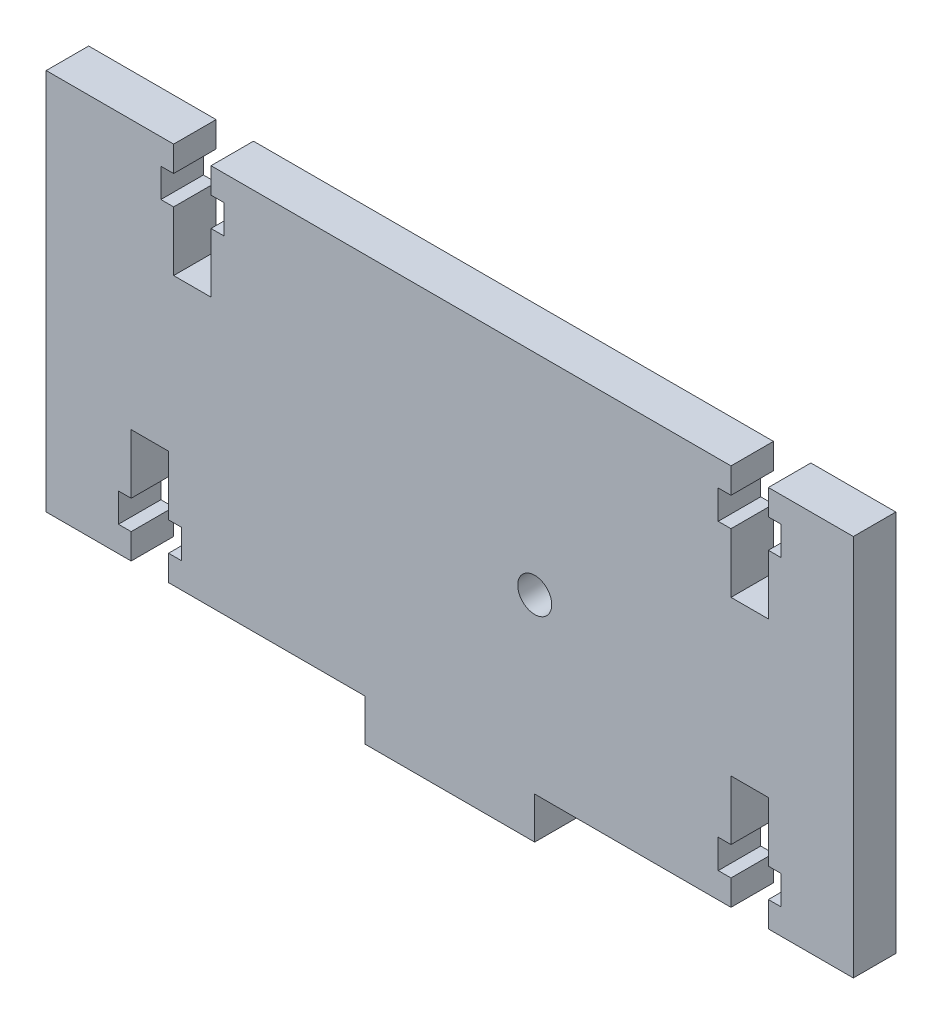
SolidWorks part; units mm, degrees
ref_plane "Front Plane" through (0, 0, 0) normal (0, 0, 1) x (1, 0, 0)
ref_plane "Top Plane" through (0, 0, 0) normal (0, 1, 0) x (1, 0, 0)
ref_plane "Right Plane" through (0, 0, 0) normal (1, 0, 0) x (0, 0, -1)
sketch "Sketch1" plane through (0, 0, 0) normal (0, 0, 1) x (1, 0, 0)
  line L0 (10, -22.5) -> (47.5, -22.5)
  line L1 (-47.5, 22.5) -> (47.5, 22.5)
  line L2 (-47.5, 22.5) -> (-47.5, -22.5)
  line L3 (-47.5, -22.5) -> (-10, -22.5)
  line L4 (47.5, 22.5) -> (47.5, -22.5)
  line L6 (-10, -22.5) -> (-10, -27.4)
  line L7 (-10, -27.4) -> (10, -27.4)
  line L8 (10, -22.5) -> (10, -27.4)
  dimension "D1" = 95
  dimension "D2" = 45
  dimension "D3" = 22.5
  dimension "D4" = 47.5
  dimension "D5" = 4.9
  dimension "D6" = 20
  dimension "D7" = 37.5
extrude "Boss-Extrude1" add sketch "Sketch1" along normal blind 5
sketch "Sketch3" plane through (0, 0, 5) normal (0, 0, 1) x (1, 0, 0)
  line L0 (-35.3, -30) -> (-35.3, -15.1548) construction
  line L1 (-33.1, -19.5) -> (-33.1, -22.5)
  line L2 (-37.5, -16.1) -> (-37.5, -9.1)
  line L3 (-31.6, -16.1) -> (-33.1, -16.1)
  line L4 (-31.6, -19.5) -> (-31.6, -16.1)
  line L5 (-33.1, -19.5) -> (-31.6, -19.5)
  line L6 (-39, -16.1) -> (-37.5, -16.1)
  line L7 (-39, -19.5) -> (-39, -16.1)
  line L8 (-37.5, -19.5) -> (-39, -19.5)
  line L9 (-37.5, -22.5) -> (-33.1, -22.5)
  line L10 (-33.1, -9.1) -> (-33.1, -16.1)
  line L11 (-37.5, -9.1) -> (-33.1, -9.1)
  line L12 (-37.5, -22.5) -> (-37.5, -19.5)
  line L13 (-47.5, -22.5) -> (-10, -22.5) construction
  line L14 (-47.5, 22.5) -> (-47.5, -22.5) construction
  line L15 (0, 0) -> (0, -21.795) construction
  line L16 (0, 0) -> (26.8997, 0) construction
  line L17 (35.3, -30) -> (35.3, -15.1548) construction
  line L18 (37.5, -22.5) -> (37.5, -19.5)
  line L19 (37.5, -9.1) -> (33.1, -9.1)
  line L20 (33.1, -9.1) -> (33.1, -16.1)
  line L21 (37.5, -22.5) -> (33.1, -22.5)
  line L22 (37.5, -19.5) -> (39, -19.5)
  line L23 (39, -19.5) -> (39, -16.1)
  line L24 (39, -16.1) -> (37.5, -16.1)
  line L25 (33.1, -19.5) -> (31.6, -19.5)
  line L26 (31.6, -19.5) -> (31.6, -16.1)
  line L27 (31.6, -16.1) -> (33.1, -16.1)
  line L28 (37.5, -16.1) -> (37.5, -9.1)
  line L29 (33.1, -19.5) -> (33.1, -22.5)
  line L30 (35.3, 30) -> (35.3, 15.1548) construction
  line L31 (33.1, 19.5) -> (33.1, 22.5)
  line L32 (37.5, 16.1) -> (37.5, 9.1)
  line L33 (31.6, 16.1) -> (33.1, 16.1)
  line L34 (31.6, 19.5) -> (31.6, 16.1)
  line L35 (33.1, 19.5) -> (31.6, 19.5)
  line L36 (39, 16.1) -> (37.5, 16.1)
  line L37 (39, 19.5) -> (39, 16.1)
  line L38 (37.5, 19.5) -> (39, 19.5)
  line L39 (37.5, 22.5) -> (33.1, 22.5)
  line L40 (33.1, 9.1) -> (33.1, 16.1)
  line L41 (37.5, 9.1) -> (33.1, 9.1)
  line L42 (37.5, 22.5) -> (37.5, 19.5)
  line L43 (-23.9141, 22.7321) -> (-23.9141, 7.8869) construction
  line L56 (-32.5, 19.5) -> (-32.5, 22.5)
  line L57 (-28.1, 16.1) -> (-28.1, 9.1)
  line L58 (-34, 16.1) -> (-32.5, 16.1)
  line L59 (-34, 19.5) -> (-34, 16.1)
  line L60 (-32.5, 19.5) -> (-34, 19.5)
  line L61 (-26.6, 16.1) -> (-28.1, 16.1)
  line L62 (-26.6, 19.5) -> (-26.6, 16.1)
  line L63 (-28.1, 19.5) -> (-26.6, 19.5)
  line L64 (-28.1, 22.5) -> (-32.5, 22.5)
  line L65 (-32.5, 9.1) -> (-32.5, 16.1)
  line L66 (-28.1, 9.1) -> (-32.5, 9.1)
  line L67 (-28.1, 22.5) -> (-28.1, 19.5)
  line L68 (47.5, 22.5) -> (-47.5, 22.5) construction
  point P66 (-28.1, 21)
  dimension "D1" = 7
  dimension "D2" = 3.4
  dimension "D3" = 3
  dimension "D4" = 2.2
  dimension "D5" = 4.4
  dimension "D6" = 1.5
  dimension "D7" = 1.5
  dimension "D8" = 10
  dimension "D9" = 15
  dimension "D10" = 3
  dimension "D11" = 3
  dimension "D12" = 3.4
  dimension "D13" = 7
  dimension "D14" = 4.4
extrude "Cut-Extrude1" cut sketch "Sketch3" against normal blind 5
sketch "Sketch4" plane through (0, 0, 5) normal (0, 0, 1) x (1, 0, 0)
  line L0 (10, -22.5) -> (33.1, -22.5) construction
  circle A0 centre (10, -2.2) radius 2
  dimension "D1" = 4
  dimension "D2" = 20.3
extrude "Cut-Extrude2" cut sketch "Sketch4" against normal blind 5
